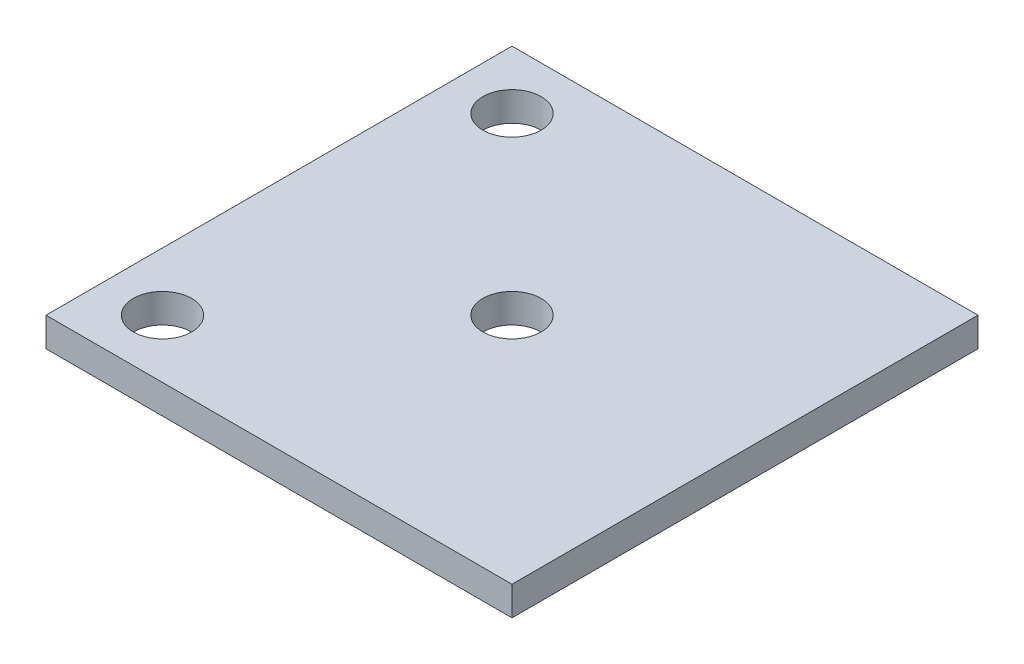
SolidWorks part; units mm, degrees
material "6061-T6 (SS)"
ref_plane "Front Plane" through (0, 0, 0) normal (0, 0, 1) x (1, 0, 0)
ref_plane "Top Plane" through (0, 0, 0) normal (0, 1, 0) x (1, 0, 0)
ref_plane "Right Plane" through (0, 0, 0) normal (1, 0, 0) x (0, 0, -1)
sketch "Sketch1" plane through (0, 0, 0) normal (0, 1, 0) x (1, 0, 0)
  line L1 (0, 0) -> (50.8, 0)
  line L2 (0, 0) -> (0, 50.8)
  line L3 (0, 50.8) -> (50.8, 50.8)
  line L4 (50.8, 0) -> (50.8, 50.8)
  line L5 (0, 0) -> (50.8, 50.8) construction
  line L6 (0, 50.8) -> (50.8, 0) construction
  point P4 (25.4, 25.4)
extrude "Boss-Extrude1" add sketch "Sketch1" along normal blind 3.175
sketch "Sketch2" plane through (0, 3.175, 0) normal (0, 1, 0) x (1, 0, 0)
  line L0 (50.8, 50.8) -> (0, 50.8) construction
  line L1 (0, 50.8) -> (0, 0) construction
  circle A0 centre (6.35, 44.45) radius 3.175
  circle A1 centre (6.35, 6.35) radius 3.175
  circle A2 centre (25.4, 25.4) radius 3.175
  dimension "D1" = 38.1
  dimension "D2" = 6.35
  dimension "D3" = 6.35
  dimension "D4" = 6.35
  dimension "D5" = 19.05
  dimension "D6" = 19.05
extrude "Cut-Extrude1" cut sketch "Sketch2" against normal blind 3.175
